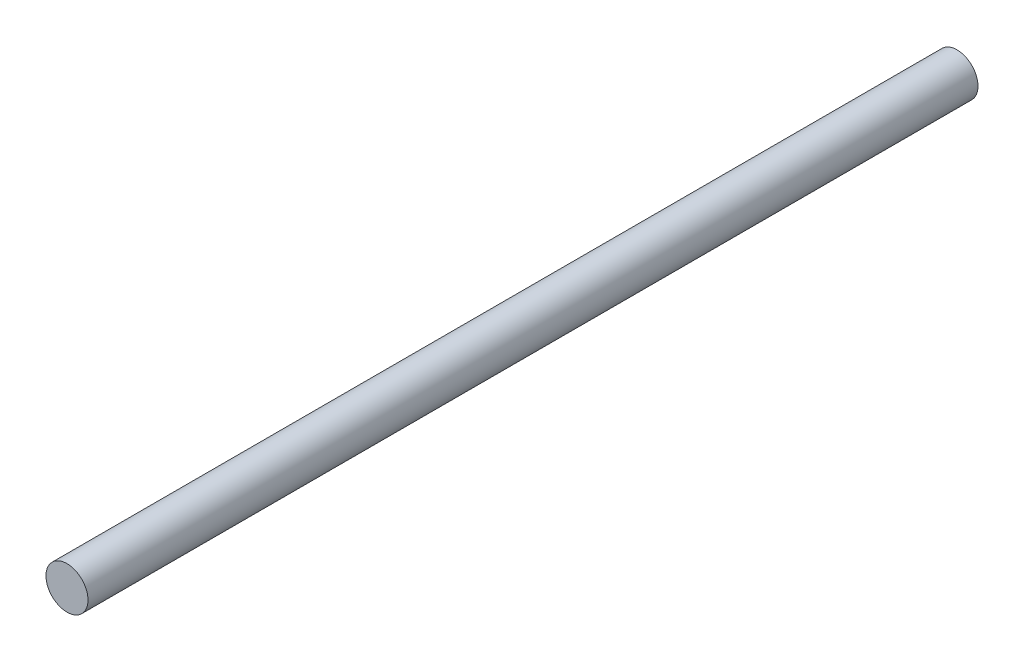
SolidWorks part; units mm, degrees
material "Plain Carbon Steel"
ref_plane "Front Plane" through (0, 0, 0) normal (0, 0, 1) x (1, 0, 0)
ref_plane "Top Plane" through (0, 0, 0) normal (0, 1, 0) x (1, 0, 0)
ref_plane "Right Plane" through (0, 0, 0) normal (1, 0, 0) x (0, 0, -1)
sketch "Sketch1" plane through (0, 0, 0) normal (0, 0, 1) x (1, 0, 0)
  circle A0 centre (0, 0) radius 3
  dimension "D1" = 6
extrude "Boss-Extrude1" add sketch "Sketch1" along normal blind 127
sketch "Sketch2" plane through (0, 0, 0) normal (0, 1, 0) x (1, 0, 0)
  line L0 (0, 0) -> (0, -127) construction
  line L1 (-3, -127) -> (3, -127) construction
  line L2 (3, -127) -> (3, 0) construction
  line L3 (3, -0.7938) -> (2.5, -0.7938)
  line L4 (3, -0.7938) -> (3, -1.5304)
  line L5 (3, -1.5304) -> (2.5, -1.5304)
  line L6 (2.5, -0.7938) -> (2.5, -1.5304)
  line L7 (3, 0) -> (-3, 0) construction
  line L8 (3, -7.8804) -> (2.5, -7.8803)
  line L9 (3, -7.8804) -> (3, -8.6169)
  line L10 (3, -8.6169) -> (2.5, -8.6169)
  line L11 (2.5, -7.8803) -> (2.5, -8.6169)
  line L12 (3, -14.9669) -> (2.5, -14.9669)
  line L13 (3, -14.9669) -> (3, -15.7035)
  line L14 (3, -15.7035) -> (2.5, -15.7035)
  line L15 (2.5, -14.9669) -> (2.5, -15.7035)
  line L16 (3, -22.0535) -> (2.5, -22.0535)
  line L17 (3, -22.0535) -> (3, -22.7901)
  line L18 (3, -22.7901) -> (2.5, -22.7901)
  line L19 (2.5, -22.0535) -> (2.5, -22.7901)
  line L20 (3, -29.1401) -> (2.5, -29.1401)
  line L21 (3, -29.1401) -> (3, -29.8767)
  line L22 (3, -29.8767) -> (2.5, -29.8767)
  line L23 (2.5, -29.1401) -> (2.5, -29.8767)
  line L24 (2.5, -29.1401) -> (2.5, -22.7901) construction
  line L25 (3, -119.1196) -> (2.5, -119.1196)
  line L26 (3, -126.2062) -> (2.5, -126.2062)
  line L27 (3, -126.2062) -> (3, -125.4696)
  line L28 (3, -125.4696) -> (2.5, -125.4696)
  line L29 (2.5, -126.2062) -> (2.5, -125.4696)
  line L30 (3, -119.1196) -> (3, -118.383)
  line L31 (3, -118.383) -> (2.5, -118.383)
  line L32 (2.5, -119.1196) -> (2.5, -118.383)
  dimension "D1" = 0.7937
  dimension "D2" = 0.7366
  dimension "D3" = 0.5
  dimension "D5" = 6.35
  dimension "D6" = 0.7937
  dimension "D8" = 6.35
  dimension "D4" = 5
  dimension "D7" = 2
revolve "Cut-Revolve1" [suppressed] cut sketch "Sketch2" angle 360 about L0
